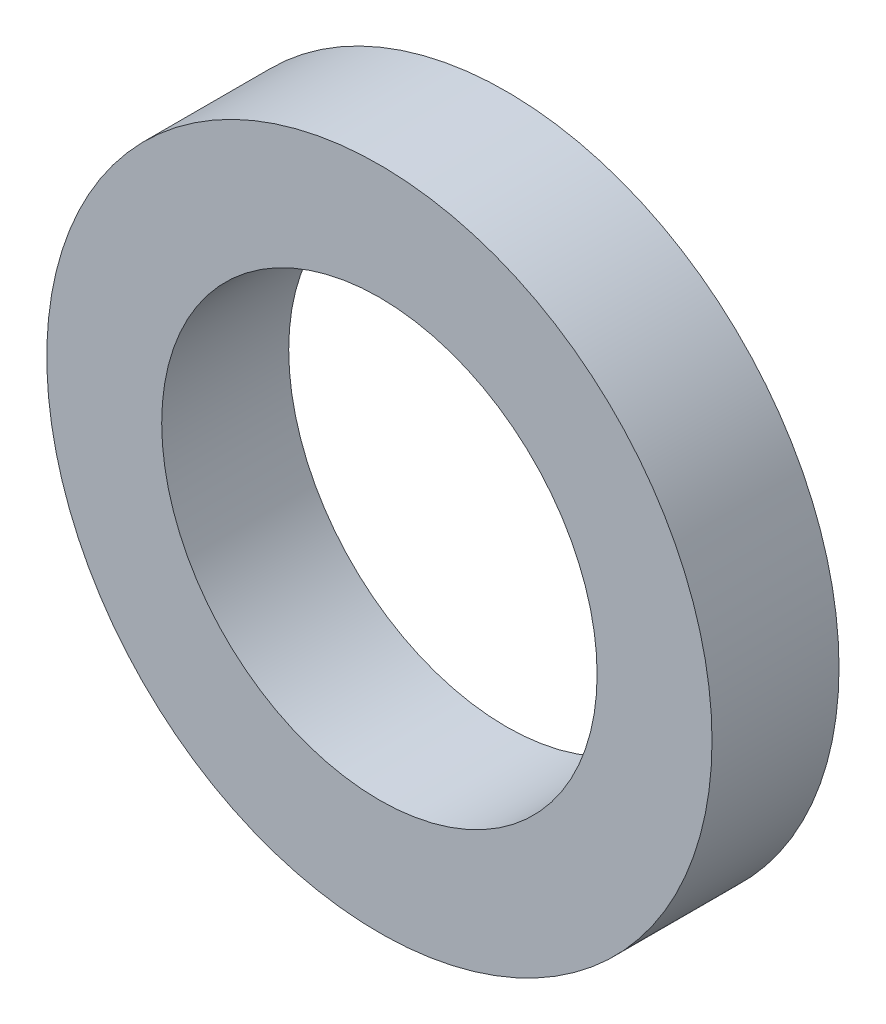
SolidWorks part; units mm, degrees
ref_plane "Front Plane" through (0, 0, 0) normal (0, 0, 1) x (1, 0, 0)
ref_plane "Top Plane" through (0, 0, 0) normal (0, 1, 0) x (1, 0, 0)
ref_plane "Right Plane" through (0, 0, 0) normal (1, 0, 0) x (0, 0, -1)
sketch "Sketch1" plane through (0, 0, 0) normal (0, 0, 1) x (1, 0, 0)
  circle A0 centre (0, 0) radius 13.97
  circle A1 centre (0, 0) radius 9.144
  dimension "D1" = 27.94
  dimension "D2" = 18.288
extrude "Boss-Extrude1" add sketch "Sketch1" along normal mid plane 5.334
